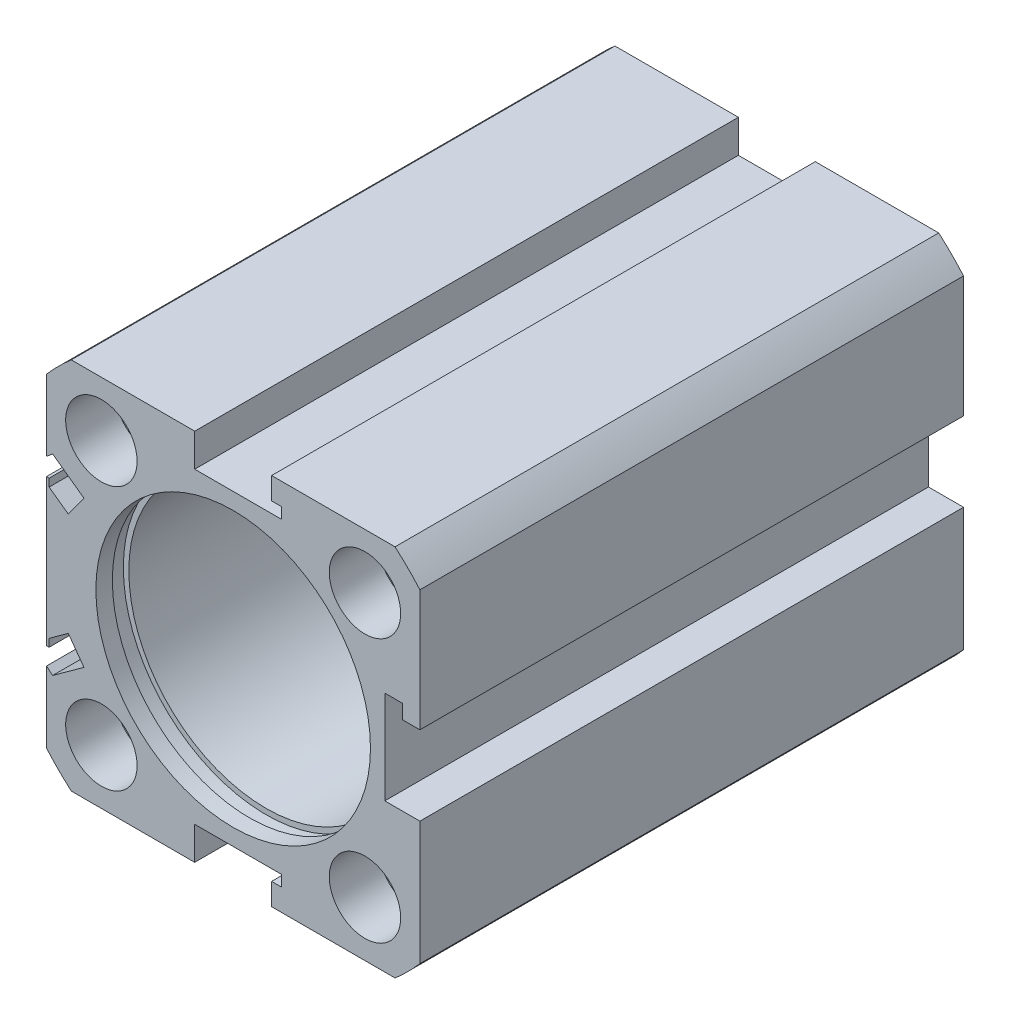
SolidWorks part; units mm, degrees
ref_plane "前视基准面" through (0, 0, 0) normal (0, 0, 1) x (1, 0, 0)
ref_plane "上视基准面" through (0, 0, 0) normal (0, 1, 0) x (1, 0, 0)
ref_plane "右视基准面" through (0, 0, 0) normal (1, 0, 0) x (0, 0, -1)
sketch "草图1" plane through (0, 0, 0) normal (0, 0, 1) x (1, 0, 0)
  line L0 (-17, 8.2688) -> (-16.4343, 8.7302)
  line L1 (-14.7394, -17) -> (-3.5, -17)
  line L2 (-17, -14.7394) -> (-17, -8.2688)
  line L3 (-14.7394, 17) -> (-3.5, 17)
  line L4 (17, -14.7394) -> (17, -3.5)
  line L5 (-18.805, -18.805) -> (18.7883, 18.7883) construction
  line L6 (-15, 15) -> (15, -15) construction
  line L7 (-3.5, 17) -> (-3.5, 14)
  line L8 (-3.5, 14) -> (4.4229, 14)
  line L9 (4.4229, 14) -> (4.4229, 15)
  line L10 (4.4229, 15) -> (3.5, 15)
  line L11 (3.5, 15) -> (3.5, 17)
  line L12 (0, 0) -> (9.3541, 0) construction
  line L13 (3.5, -15) -> (3.5, -17)
  line L14 (4.4229, -15) -> (3.5, -15)
  line L15 (4.4229, -14) -> (4.4229, -15)
  line L16 (-3.5, -17) -> (-3.5, -14)
  line L17 (-3.5, -14) -> (4.4229, -14)
  line L18 (17, -3.5) -> (13.805, -3.5)
  line L19 (13.805, -3.5) -> (13.805, 5)
  line L20 (13.805, 5) -> (15.4025, 5)
  line L21 (15.4025, 5) -> (15.4025, 3.7)
  line L22 (15.4025, 3.7) -> (17, 3.7)
  line L23 (3.5, -17) -> (14.7394, -17)
  line L24 (-16.4343, 8.7302) -> (-13.5852, 6.6692)
  line L25 (-13.5852, 6.6692) -> (-15.0098, 4.7)
  line L26 (-15.0098, 4.7) -> (-16.7565, 5.9636)
  line L27 (-16.7565, 5.9636) -> (-16.7565, 6.6692)
  line L28 (-16.7565, 6.6692) -> (-17, 6.6692)
  line L29 (-17, 0) -> (5.5944, 0) construction
  line L30 (-17, -8.2688) -> (-16.4343, -8.7302)
  line L31 (-16.4343, -8.7302) -> (-13.5852, -6.6692)
  line L32 (-13.5852, -6.6692) -> (-15.0098, -4.7)
  line L33 (-15.0098, -4.7) -> (-16.7565, -5.9636)
  line L34 (-16.7565, -5.9636) -> (-16.7565, -6.6692)
  line L35 (-16.7565, -6.6692) -> (-17, -6.6692)
  line L36 (3.5, 17) -> (14.7394, 17)
  line L37 (17, 3.7) -> (17, 14.7394)
  line L38 (-17, -6.6692) -> (-17, 6.6692)
  line L39 (-17, 8.2688) -> (-17, 14.7394)
  line L40 (0, 0) -> (0, 20.1809) construction
  arc A0 (-17, -14.7394) -> (-14.7394, -17) centre (0, 0) ccw
  circle A1 centre (0, 0) radius 12.5
  arc A2 (14.7394, -17) -> (17, -14.7394) centre (0, 0) ccw
  arc A3 (17, 14.7394) -> (14.7394, 17) centre (0, 0) ccw
  arc A4 (-14.7394, 17) -> (-17, 14.7394) centre (0, 0) ccw
  circle A5 centre (12, 12) radius 2.1
  circle A6 centre (-12, 12) radius 2.1
  circle A7 centre (-12, -12) radius 2.1
  circle A8 centre (12, -12) radius 2.1
  dimension "D1" = 45
  dimension "D11" = 25
  dimension "D12" = 4.2
  dimension "D13" = 4.2
  dimension "D14" = 4.2
  dimension "D15" = 4.2
  dimension "D16" = 12
  dimension "D17" = 12
  dimension "D18" = 12
  dimension "D21" = 12
  dimension "D22" = 12
  dimension "D23" = 12
  dimension "D2" = 34
  dimension "D3" = 34
  dimension "D4" = 13.5
  dimension "D5" = 7
  dimension "D6" = 3
  dimension "D7" = 2
  dimension "D8" = 8.5
  dimension "D9" = 13.5
  dimension "D10" = 7.2
  dimension "D19" = 12
  dimension "D20" = 12
extrude "拉伸1" add sketch "草图1" along normal blind 49.5
sketch "草图2" plane through (0, 0, 49.5) normal (0, 0, 1) x (1, 0, 0)
  circle A0 centre (-12, 12) radius 3.25
  circle A1 centre (12, 12) radius 3.25
  circle A2 centre (12, -12) radius 3.25
  circle A3 centre (-12, -12) radius 3.25
  dimension "D1" = 6.5
extrude "拉伸2" cut sketch "草图2" against normal blind 4.5
ref_plane "基准面1" through (0, 0, 24.75) normal (0, 0, 1) x (1, 0, 0)
sketch "草图4" plane through (0, 0, 0) normal (0, 1, 0) x (1, 0, 0)
  line L0 (0, 0) -> (0, -49.5) construction
  line L1 (13, -1.5) -> (13, -3)
  line L2 (13, -3) -> (0, -3)
  line L3 (0, -3) -> (0, -1.5)
  line L4 (12.5, 0) -> (-12.5, 0) construction
  line L5 (13, -1.5) -> (0, -1.5)
  line L8 (13, -48) -> (13, -46.5)
  line L9 (13, -46.5) -> (0, -46.5)
  line L10 (0, -46.5) -> (0, -48)
  line L11 (13, -48) -> (0, -48)
  line L12 (-12.5, -49.5) -> (12.5, -49.5) construction
  dimension "D1" = 1.5
  dimension "D2" = 1.5
revolve "切除-旋转1" cut sketch "草图4" angle 360 about L0
mirror "镜向1" about plane through (0, 0, 24.75) normal (0, 0, 1) of "拉伸2"
sketch "草图5" plane through (-17, 0, 0) normal (-1, 0, 0) x (0, 0, 1)
  line L0 (0, 0) -> (49.5, 0) construction
  line L1 (49.5, 6.6692) -> (49.5, -6.6692) construction
  line L2 (24.75, -18.7) -> (24.75, 18.7) construction
  line L3 (24.75, 0) -> (24.75, 10.4901) construction
  circle A0 centre (7.25, 0) radius 2.1
  circle A1 centre (42.25, 0) radius 2.1
  dimension "D1" = 35
  dimension "D2" = 4.2
extrude "拉伸3" cut sketch "草图5" against normal blind 4
